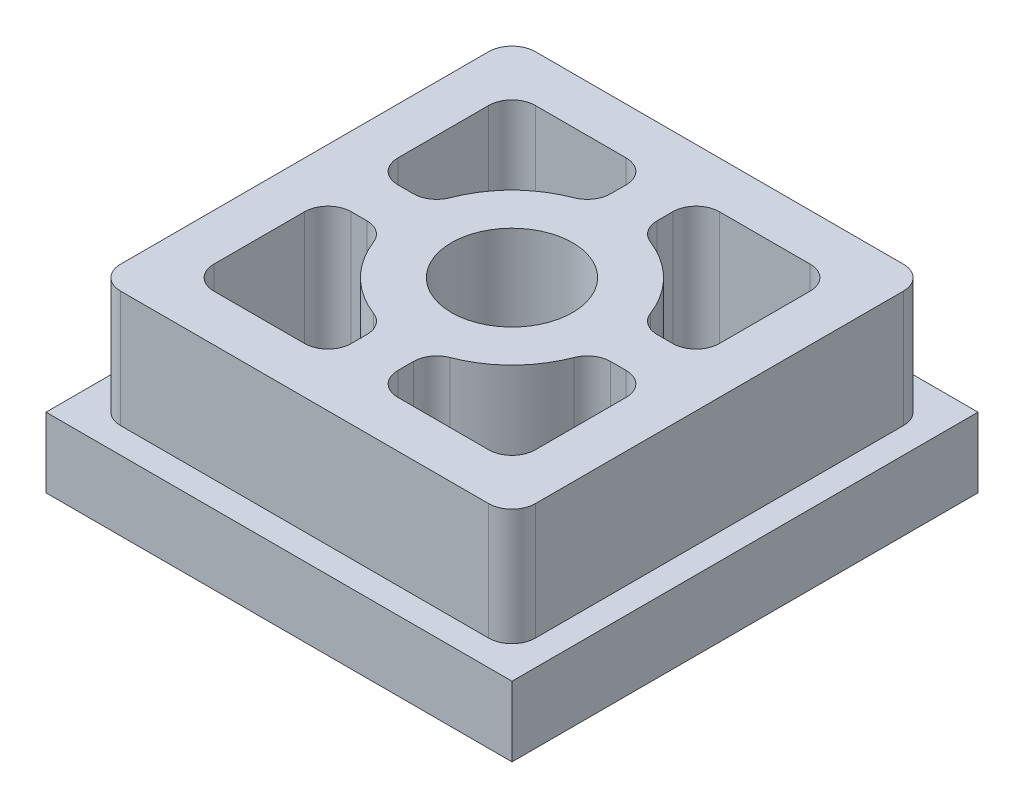
SolidWorks part; units mm, degrees
material "POM 乙缩醛共聚物"
ref_plane "前视基准面" through (0, 0, 0) normal (0, 0, 1) x (1, 0, 0)
ref_plane "上视基准面" through (0, 0, 0) normal (0, 1, 0) x (1, 0, 0)
ref_plane "右视基准面" through (0, 0, 0) normal (1, 0, 0) x (0, 0, -1)
sketch "草图1" plane through (0, 0, 0) normal (0, 1, 0) x (1, 0, 0)
  line L1 (-10, -10) -> (10, -10)
  line L2 (-10, -10) -> (-10, 10)
  line L3 (-10, 10) -> (10, 10)
  line L4 (10, -10) -> (10, 10)
  line L5 (0, 10) -> (0, -10) construction
  line L6 (-10, 0) -> (10, 0) construction
  point P0 (0, 0)
  dimension "D1" = 20
extrude "凸台-拉伸1" add sketch "草图1" along normal blind 3
sketch "草图2" plane through (0, 3, 0) normal (0, 1, 0) x (1, 0, 0)
  line L1 (-8.9, -8.9) -> (8.9, -8.9)
  line L2 (-8.9, -8.9) -> (-8.9, 8.9)
  line L3 (-8.9, 8.9) -> (8.9, 8.9)
  line L4 (8.9, -8.9) -> (8.9, 8.9)
  line L5 (0, 8.9) -> (0, -8.9) construction
  line L6 (-8.9, 0) -> (8.9, 0) construction
  point P0 (0, 0)
  dimension "D1" = 17.8
extrude "凸台-拉伸2" add sketch "草图2" along normal blind 5
sketch "草图3" plane through (0, 8, 0) normal (0, 1, 0) x (1, 0, 0)
  circle A0 centre (0, 0) radius 2.6
  dimension "D1" = 5.2
extrude "切除-拉伸1" cut sketch "草图3" against normal through all
sketch "草图4" plane through (0, 8, 0) normal (0, 1, 0) x (1, 0, 0)
  line L4 (-6.9, 0) -> (-4.6, 0) construction
  line L5 (-6.9, -1) -> (-4.49, -1)
  line L6 (-6.9, 1) -> (-4.49, 1)
  line L7 (1, 6.9) -> (1, 4.49)
  line L8 (6.9, -6.9) -> (6.9, 6.9)
  line L9 (6.9, 6.9) -> (-6.9, 6.9)
  line L10 (-6.9, 6.9) -> (-6.9, -6.9)
  line L11 (-6.9, -6.9) -> (6.9, -6.9)
  line L12 (6.9, -6.9) -> (6.9, 6.9)
  line L13 (6.9, 6.9) -> (-6.9, 6.9)
  line L14 (-6.9, 6.9) -> (-6.9, -6.9)
  line L15 (-6.9, -6.9) -> (6.9, -6.9)
  line L16 (-1, 6.9) -> (-1, 4.49)
  line L17 (6.9, -1) -> (4.49, -1)
  line L18 (6.9, 1) -> (4.49, 1)
  line L19 (-1, -6.9) -> (-1, -4.49)
  line L20 (1, -6.9) -> (1, -4.49)
  circle A2 centre (0, 0) radius 4.6
  circle A3 centre (0, 0) radius 4.6
  point P28 (0, 0)
  dimension "D3" = 2
  dimension "D1" = 2
  dimension "D2" = 2
  dimension "D4" = 4
extrude "切除-拉伸2" cut sketch "草图4" against normal blind 10 contours A3 L5 L14 L15 L19 | A3 L16 L13 L14 L6 | A3 L20 L15 L12 L17 | A3 L18 L12 L13 L7
fillet "圆角1" radius 1 20 edges at (-6.9, 4, -1) (-1, 4, -6.9) (-1, 4, -4.49) (-4.49, 4, -1) (6.9, 4, 1) (6.9, 4, 6.9) (1, 4, 6.9) (1, 4, 4.49) (4.49, 4, 1) (1, 4, -6.9) (6.9, 4, -6.9) (6.9, 4, -1) (4.49, 4, -1) (1, 4, -4.49) (-1, 4, 6.9) (-6.9, 4, 6.9) (-6.9, 4, 1) (-4.49, 4, 1) (-1, 4, 4.49) (-6.9, 4, -6.9)
fillet "圆角2" radius 1 4 edges at (8.9, 5.5, 8.9) (-8.9, 5.5, -8.9) (8.9, 5.5, -8.9) (-8.9, 5.5, 8.9)
move or copy body "实体-移动/复制1" [suppressed] bodies to move or copy 110
